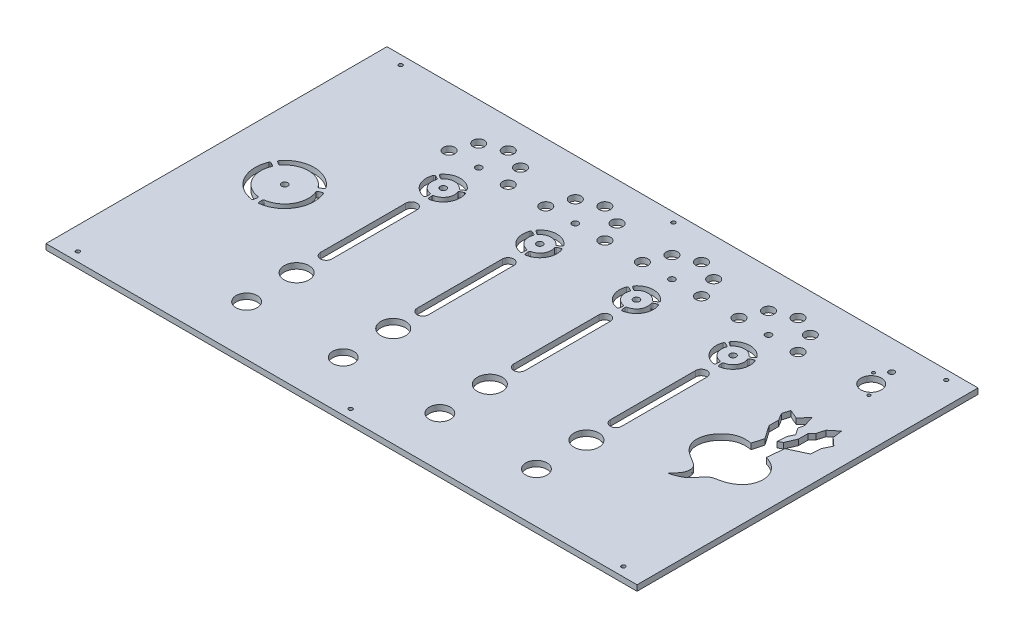
SolidWorks part; units mm, degrees
ref_plane "Front Plane" through (0, 0, 0) normal (0, 0, 1) x (1, 0, 0)
ref_plane "Top Plane" through (0, 0, 0) normal (0, 1, 0) x (1, 0, 0)
ref_plane "Right Plane" through (0, 0, 0) normal (1, 0, 0) x (0, 0, -1)
sketch "Sketch1" plane through (0, 0, 0) normal (0, 1, 0) x (1, 0, 0)
  line L1 (-330.2, 190.5) -> (330.2, 190.5)
  line L2 (-330.2, 190.5) -> (-330.2, -190.5)
  line L3 (-330.2, -190.5) -> (330.2, -190.5)
  line L4 (330.2, 190.5) -> (330.2, -190.5)
  line L5 (-330.2, 190.5) -> (330.2, -190.5) construction
  line L6 (-330.2, -190.5) -> (330.2, 190.5) construction
  point P0 (0, 0)
  dimension "D1" = 660.4
  dimension "D2" = 381
extrude "Boss-Extrude1" add sketch "Sketch1" along normal blind 6.35
sketch "Sketch2" plane through (0, 6.35, 0) normal (0, 1, 0) x (1, 0, 0)
  line L0 (-161.925, 49.53) -> (-161.925, -45.72) construction
  line L1 (-155.575, 49.53) -> (-155.575, -45.72)
  line L2 (-168.275, 49.53) -> (-168.275, -45.72)
  line L3 (-330.2, -190.5) -> (330.2, -190.5) construction
  line L4 (-330.2, 190.5) -> (-330.2, -190.5) construction
  circle A0 centre (-161.925, -134.62) radius 11.811
  circle A1 centre (-161.925, -78.74) radius 13.843
  circle A2 centre (-161.925, 85.09) radius 3.429
  circle A3 centre (-161.925, 124.714) radius 3.429
  circle A4 centre (-194.945, 124.714) radius 6.35
  circle A5 centre (-185.2737, 148.0627) radius 6.35
  circle A6 centre (-161.925, 157.734) radius 6.35
  circle A7 centre (-138.5763, 148.0627) radius 6.35
  circle A8 centre (-128.905, 124.714) radius 6.35
  arc A9 (-155.575, 49.53) -> (-168.275, 49.53) centre (-161.925, 49.53) ccw
  arc A10 (-168.275, -45.72) -> (-155.575, -45.72) centre (-161.925, -45.72) ccw
  circle A11 centre (-161.925, 124.714) radius 3.429
  circle A12 centre (-161.925, 124.714) radius 3.429
  circle A13 centre (-161.925, 124.714) radius 3.429
  circle A14 centre (-161.925, 124.714) radius 3.429
  circle A15 centre (-170.561, 130.556) radius 1.397
  circle A16 centre (-170.561, 113.792) radius 1.397
  circle A17 centre (-161.925, 85.09) radius 19.05
  circle A18 centre (-161.925, 124.714) radius 8.89
  circle A19 centre (-161.925, 85.09) radius 8.89
  circle A20 centre (-161.925, -134.62) radius 30.099
  circle A21 centre (-161.925, -78.74) radius 16.637
  point P11 (-161.925, 1.905)
  point P20 (-161.925, 124.714)
  dimension "D2" = 23.622
  dimension "D3" = 27.686
  dimension "D4" = 12.7
  dimension "D7" = 6.858
  dimension "D8" = 6.858
  dimension "D9" = 2.794
  dimension "D10" = 16.764
  dimension "D19" = 38.1
  dimension "D20" = 17.78
  dimension "D21" = 17.78
  dimension "D17" = 33.02
  dimension "D23" = 60.198
  dimension "D24" = 33.274
  dimension "D5" = 95.25
  dimension "D6" = 12.7
  dimension "D11" = 8.636
  dimension "D12" = 5.842
  dimension "D13" = 33.02
  dimension "D14" = 55.88
  dimension "D15" = 168.275
  dimension "D16" = 55.88
  dimension "D18" = 35.56
  dimension "D22" = 39.624
  dimension "D25" = 75.184
  dimension "D1" = 5
extrude "Cut-Extrude1" cut sketch "Sketch2" against normal through all
sketch "Sketch10" plane through (0, 6.35, 0) normal (0, 1, 0) x (1, 0, 0)
  line L0 (-161.925, 85.09) -> (-177.5298, 96.0166) construction
  line L1 (-161.925, 85.09) -> (-146.3202, 96.0166) construction
  line L2 (-176.4523, 95.2621) -> (-173.3212, 93.0697)
  line L3 (-150.5288, 93.0697) -> (-147.3977, 95.2621)
  line L4 (-145.852, 92.585) -> (-149.3163, 90.9695)
  line L5 (-160.7125, 71.2308) -> (-160.3793, 67.4229)
  line L6 (-163.4707, 67.4229) -> (-163.1375, 71.2308)
  line L7 (-174.5337, 90.9695) -> (-177.998, 92.585)
  arc A0 (-171.6229, 93.29) -> (-152.2271, 93.29) centre (-161.925, 85.09) cw
  arc A1 (-176.7095, 97.1034) -> (-147.1405, 97.1034) centre (-161.925, 85.09) cw
  arc A2 (-176.4523, 95.2621) -> (-176.7095, 97.1034) centre (-175.7239, 96.3025) cw
  arc A3 (-150.5288, 93.0697) -> (-152.2271, 93.29) centre (-151.2573, 94.11) cw
  arc A4 (-147.3977, 95.2621) -> (-147.1405, 97.1034) centre (-148.1261, 96.3025) ccw
  arc A5 (-171.6229, 93.29) -> (-173.3212, 93.0697) centre (-172.5927, 94.11) cw
  arc A6 (-144.1289, 91.8871) -> (-158.9134, 66.2796) centre (-161.925, 85.09) cw
  arc A7 (-145.852, 92.585) -> (-144.1289, 91.8871) centre (-145.3153, 91.4339) cw
  arc A8 (-149.9746, 89.3887) -> (-159.6726, 72.5913) centre (-161.925, 85.09) cw
  arc A9 (-149.9746, 89.3887) -> (-149.3163, 90.9695) centre (-148.7796, 89.8185) cw
  arc A10 (-160.7125, 71.2308) -> (-159.6726, 72.5913) centre (-159.4473, 71.3415) cw
  arc A11 (-160.3793, 67.4229) -> (-158.9134, 66.2796) centre (-159.1142, 67.5336) ccw
  arc A12 (-164.9366, 66.2796) -> (-179.7211, 91.8871) centre (-161.925, 85.09) cw
  arc A13 (-163.4707, 67.4229) -> (-164.9366, 66.2796) centre (-164.7358, 67.5336) cw
  arc A14 (-164.1774, 72.5913) -> (-173.8754, 89.3887) centre (-161.925, 85.09) cw
  arc A15 (-164.1774, 72.5913) -> (-163.1375, 71.2308) centre (-164.4027, 71.3415) cw
  arc A16 (-174.5337, 90.9695) -> (-173.8754, 89.3887) centre (-175.0704, 89.8185) cw
  arc A17 (-177.998, 92.585) -> (-179.7211, 91.8871) centre (-178.5347, 91.4339) ccw
  point P11 (-151.5218, 92.3744)
  point P17 (-172.3282, 92.3744)
  point P44 (-161.925, 85.09)
  dimension "D2" = 12.7
  dimension "D3" = 19.05
  dimension "D4" = 1.27
  dimension "D1" = 110
  dimension "D5" = 3
extrude "Cut-Extrude9" cut sketch "Sketch10" against normal through all
pattern_linear "LPattern1" count 4 spacing 107.95 along (1, 0, 0) of "Cut-Extrude1", "Cut-Extrude9"
sketch "Sketch5" plane through (0, 6.35, 0) normal (0, 1, 0) x (1, 0, 0)
  line L0 (-281.0484, 18.9395) -> (-254, 0) construction
  line L1 (-254, 0) -> (-226.9516, 18.9395) construction
  line L2 (-254, 0) -> (-254, 46.9935) construction
  line L3 (-279.9873, 18.1965) -> (-276.8635, 16.0092)
  line L4 (-231.1365, 16.0092) -> (-228.0127, 18.1965)
  line L5 (-225.2478, 13.4074) -> (-228.7039, 11.7957)
  line L6 (-251.5674, -27.8049) -> (-251.235, -31.6039)
  line L7 (-256.765, -31.6039) -> (-256.4326, -27.8049)
  line L8 (-279.2961, 11.7957) -> (-282.7522, 13.4074)
  line L9 (-330.2, 190.5) -> (-330.2, -190.5) construction
  circle A0 centre (-254, 0) radius 3.429
  circle A1 centre (-254, 0) radius 17.78
  arc A2 (-223.5395, 12.7466) -> (-249.8086, -32.7529) centre (-254, 0) cw
  arc A3 (-275.1289, 16.2745) -> (-232.8711, 16.2745) centre (-254, 0) cw
  arc A4 (-280.2692, 20.0063) -> (-227.7308, 20.0063) centre (-254, 0) cw
  arc A5 (-229.3414, 10.1609) -> (-250.4703, -26.4354) centre (-254, 0) cw
  arc A6 (-258.1914, -32.7529) -> (-284.4605, 12.7466) centre (-254, 0) cw
  arc A7 (-257.5297, -26.4354) -> (-278.6586, 10.1609) centre (-254, 0) cw
  arc A8 (-279.2961, 11.7957) -> (-278.6586, 10.1609) centre (-279.8328, 10.6447) cw
  arc A9 (-282.7522, 13.4074) -> (-284.4605, 12.7466) centre (-283.289, 12.2564) ccw
  arc A10 (-258.1914, -32.7529) -> (-256.765, -31.6039) centre (-258.0301, -31.4932) ccw
  arc A11 (-257.5297, -26.4354) -> (-256.4326, -27.8049) centre (-257.6978, -27.6942) cw
  arc A12 (-249.8086, -32.7529) -> (-251.235, -31.6039) centre (-249.9699, -31.4932) cw
  arc A13 (-250.4703, -26.4354) -> (-251.5674, -27.8049) centre (-250.3022, -27.6942) ccw
  arc A14 (-223.5395, 12.7466) -> (-225.2478, 13.4074) centre (-224.711, 12.2564) ccw
  arc A15 (-229.3414, 10.1609) -> (-228.7039, 11.7957) centre (-228.1672, 10.6447) cw
  arc A16 (-231.1365, 16.0092) -> (-232.8711, 16.2745) centre (-231.865, 17.0495) cw
  arc A17 (-228.0127, 18.1965) -> (-227.7308, 20.0063) centre (-228.7412, 19.2368) ccw
  arc A18 (-276.8635, 16.0092) -> (-275.1289, 16.2745) centre (-276.135, 17.0495) ccw
  arc A19 (-279.9873, 18.1965) -> (-280.2692, 20.0063) centre (-279.2588, 19.2368) cw
  point P22 (-254, 0)
  point P29 (-254, 0)
  point P39 (-232.1532, 15.2973)
  point P45 (-275.8468, 15.2973)
  dimension "D1" = 6.858
  dimension "D2" = 35.56
  dimension "D3" = 3
  dimension "D4" = 26.67
  dimension "D5" = 33.02
  dimension "D9" = 1.27
  dimension "D7" = 110
  dimension "D8" = 76.2
  dimension "D6" = 3
extrude "Cut-Extrude6" cut sketch "Sketch5" against normal through all
sketch "Sketch6" plane through (0, 6.35, 0) normal (0, 1, 0) x (1, 0, 0)
  line L0 (330.2, -190.5) -> (330.2, 190.5) construction
  line L1 (254, 149.86) -> (279.4, 149.86)
  line L2 (254, 149.86) -> (254, 119.38)
  line L3 (254, 119.38) -> (279.4, 119.38)
  line L4 (279.4, 149.86) -> (279.4, 119.38)
  line L5 (254, 149.86) -> (279.4, 119.38) construction
  line L6 (254, 119.38) -> (279.4, 149.86) construction
  line L7 (330.2, 190.5) -> (-330.2, 190.5) construction
  circle A0 centre (266.7, 134.62) radius 11.43
  circle A1 centre (266.7, 157.48) radius 3.175
  circle A2 centre (257.048, 146.812) radius 1.651
  circle A3 centre (276.352, 122.428) radius 1.651
  dimension "D1" = 22.86
  dimension "D2" = 6.35
  dimension "D6" = 3.302
  dimension "D9" = 3.048
  dimension "D3" = 22.86
  dimension "D4" = 25.4
  dimension "D5" = 30.48
  dimension "D7" = 3.048
  dimension "D8" = 3.048
  dimension "D10" = 3.048
  dimension "D11" = 63.5
  dimension "D12" = 55.88
extrude "Cut-Extrude7" cut sketch "Sketch6" against normal through all contours A0 | A2 | A3 | A1
sketch "Sketch7" plane through (0, 6.35, 0) normal (0, 1, 0) x (1, 0, 0)
  line L0 (255.7189, 6.2581) -> (260.2157, 22.4284)
  line L1 (260.2157, 22.4284) -> (249.9283, 37.2593)
  line L2 (249.9283, 37.2593) -> (249.9283, 48.0171)
  line L3 (249.9283, 48.0171) -> (245.0916, 55.9581)
  line L4 (245.0916, 55.9581) -> (247.51, 64.1887)
  line L5 (247.51, 64.1887) -> (257.6021, 59.8434)
  line L6 (257.6021, 59.8434) -> (266.331, 69.1607)
  line L7 (266.331, 69.1607) -> (269.778, 56.9273)
  line L8 (270.6732, 37.2593) -> (273.5917, 43.3464)
  line L9 (269.778, 26.5026) -> (274.4256, 29.1709)
  line L10 (274.4256, 29.1709) -> (279.4058, 40.7397)
  line L11 (279.4058, 40.7397) -> (279.4058, 51.0798)
  line L12 (279.4058, 51.0798) -> (283.6828, 55.9581)
  line L13 (283.6828, 55.9581) -> (286.2797, 64.796)
  line L14 (286.2797, 64.796) -> (295.7541, 72.4954)
  line L15 (295.7541, 72.4954) -> (297.3234, 61.5107)
  line L16 (297.3234, 61.5107) -> (305.9452, 53.6862)
  line L17 (305.9452, 53.6862) -> (301.2757, 43.9301)
  line L18 (301.2757, 43.9301) -> (300.4876, 32.9233)
  line L19 (300.4876, 32.9233) -> (281.0964, 23.8342)
  line L20 (281.0964, 23.8342) -> (278.9259, 1.7686)
  line L21 (278.9259, 1.7686) -> (255.7189, 6.2581)
  line L22 (269.778, 26.5026) -> (270.6732, 37.2593)
  line L23 (273.5917, 43.3464) -> (268.4218, 51.0798)
  line L24 (268.4218, 51.0798) -> (269.778, 56.9273)
  line L26 (181.5842, 43.0883) -> (224.5474, 43.0883)
  line L27 (181.5842, 43.0883) -> (181.5842, 1.7686)
  line L28 (181.5842, 1.7686) -> (224.5474, 1.7686)
  line L29 (224.5474, 43.0883) -> (224.5474, 1.7686)
  line L30 (181.5842, 43.0883) -> (224.5474, 1.7686) construction
  line L31 (181.5842, 1.7686) -> (224.5474, 43.0883) construction
  spline S0 degree 3 poles (269.8957, 7.0712) (260.2215, 9.4099) (233.6996, 17.3044) (209.0751, -25.3619) (250.4959, -43.3896) (247.3978, -60.0979) (232.6874, -67.8276) (257.5896, -59.8745) (263.392, -45.0431) (297.8507, -40.8718) (303.9159, -14.9658) (285.5677, 5.2291) (269.8957, 7.0712) (260.2215, 9.4099) (233.6996, 17.3044) knots -0.206906 -0.161359 -0.017929 0 0.112637 0.317899 0.358519 0.401499 0.459605 0.498799 0.539957 0.572148 0.793094 0.838641 0.982071 1 1.112637 1.317899 1.358519 only from (263.4579, 8.6384) to (263.4579, 8.6384)
  point P31 (203.0658, 22.4284)
  dimension "D1" = 42.9632
extrude "Cut-Extrude8" cut sketch "Sketch7" against normal through all contours L0 S0 L20 L21 | S0 L20 L19 L18 L17 L16 L15 L14 L13 L12 L11 L10 L9 L22 L8 L23 L24 L7 L6 L5 L4 L3 L2 L1 L0 | L20 S0 L0 L21
sketch "Sketch11" plane through (0, 6.35, 0) normal (0, 1, 0) x (1, 0, 0)
  line L1 (226.1466, 11.4796) -> (292.1866, 11.4796)
  line L2 (226.1466, 11.4796) -> (226.1466, -54.5604)
  line L3 (226.1466, -54.5604) -> (292.1866, -54.5604)
  line L4 (292.1866, 11.4796) -> (292.1866, -54.5604)
  line L5 (226.1466, 11.4796) -> (292.1866, -54.5604) construction
  line L6 (226.1466, -54.5604) -> (292.1866, 11.4796) construction
  line L7 (257.1608, 63.4896) -> (266.6328, 63.4896)
  line L8 (257.1608, 63.4896) -> (257.1608, 12.6896)
  line L9 (257.1608, 12.6896) -> (266.6328, 12.6896)
  line L10 (266.6328, 63.4896) -> (266.6328, 12.6896)
  line L11 (257.1608, 63.4896) -> (266.6328, 12.6896) construction
  line L12 (257.1608, 12.6896) -> (266.6328, 63.4896) construction
  point P0 (259.1666, -21.5404)
  point P7 (261.8968, 38.0896)
  dimension "D1" = 66.04
  dimension "D2" = 66.04
  dimension "D3" = 50.8
sketch "Sketch12" plane through (0, 6.35, 0) normal (0, 1, 0) x (1, 0, 0)
  line L0 (-330.2, 190.5) -> (-330.2, -190.5) construction
  line L1 (330.2, 190.5) -> (-330.2, 190.5) construction
  line L2 (330.2, -190.5) -> (330.2, 190.5) construction
  line L3 (0, 0) -> (33.8653, 0) construction
  circle A0 centre (-304.8, 180.34) radius 2.159
  circle A1 centre (0, 180.34) radius 2.159
  circle A2 centre (304.8, 180.34) radius 2.159
  circle A3 centre (304.8, -180.34) radius 2.159
  circle A4 centre (0, -180.34) radius 2.159
  circle A5 centre (-304.8, -180.34) radius 2.159
  dimension "D1" = 4.318
  dimension "D2" = 25.4
  dimension "D3" = 10.16
  dimension "D4" = 25.4
extrude "Cut-Extrude10" cut sketch "Sketch12" against normal through all
